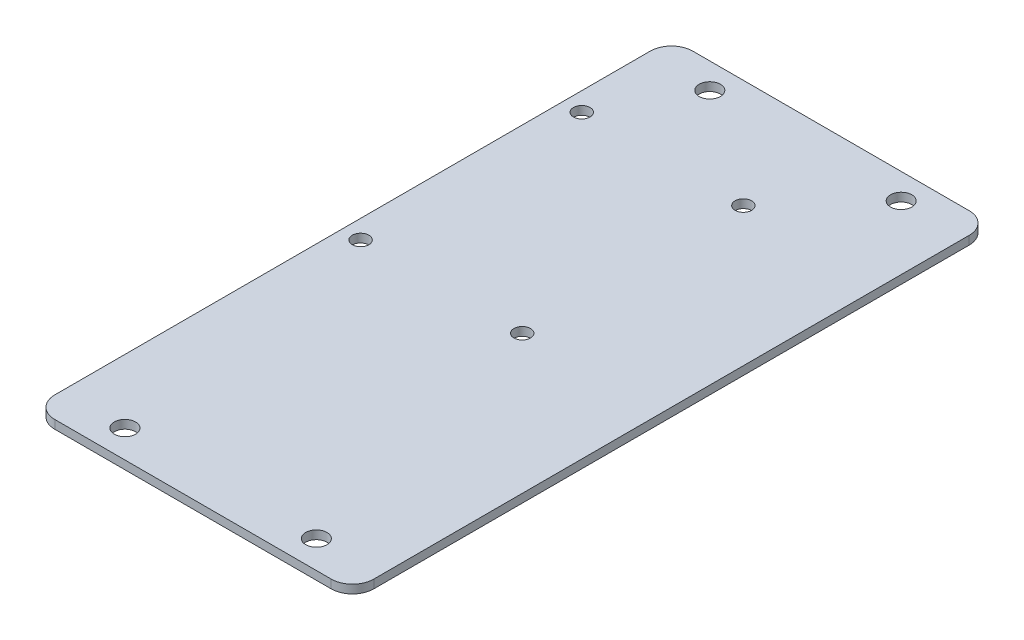
SolidWorks part; units mm, degrees
ref_plane "Front" through (0, 0, 0) normal (0, 0, 1) x (1, 0, 0)
ref_plane "Top" through (0, 0, 0) normal (0, 1, 0) x (1, 0, 0)
ref_plane "Right" through (0, 0, 0) normal (1, 0, 0) x (0, 0, -1)
sketch "Sketch1" plane through (0, 0, 0) normal (0, 1, 0) x (1, 0, 0)
  line L0 (0, 87.63) -> (0, 95.25) construction
  line L1 (-47.625, 95.25) -> (47.625, 95.25)
  line L2 (-47.625, 95.25) -> (-47.625, -95.25)
  line L3 (-47.625, -95.25) -> (47.625, -95.25)
  line L4 (47.625, 95.25) -> (47.625, -95.25)
  line L5 (-47.625, 95.25) -> (47.625, -95.25) construction
  line L6 (-47.625, -95.25) -> (47.625, 95.25) construction
  line L7 (-42.037, 62.865) -> (6.223, 62.865) construction
  line L8 (-42.037, 62.865) -> (-42.037, -3.175) construction
  line L9 (-42.037, -3.175) -> (6.223, -3.175) construction
  line L10 (6.223, 62.865) -> (6.223, -3.175) construction
  line L11 (-42.037, 62.865) -> (6.223, -3.175) construction
  line L12 (-42.037, -3.175) -> (6.223, 62.865) construction
  line L13 (-28.575, 87.63) -> (28.575, 87.63) construction
  line L14 (-28.575, 87.63) -> (-28.575, -86.995) construction
  line L15 (-28.575, -86.995) -> (28.575, -86.995) construction
  line L16 (28.575, 87.63) -> (28.575, -86.995) construction
  circle A0 centre (-42.037, 62.865) radius 2.4765
  circle A1 centre (6.223, 62.865) radius 2.4765
  circle A2 centre (6.223, -3.175) radius 2.4765
  circle A3 centre (-42.037, -3.175) radius 2.4765
  circle A4 centre (-28.575, 87.63) radius 3.175
  circle A5 centre (28.575, 87.63) radius 3.175
  circle A6 centre (28.575, -86.995) radius 3.175
  circle A7 centre (-28.575, -86.995) radius 3.175
  point P0 (0, 0)
  point P6 (-17.907, 29.845)
  point P15 (0, 0)
  point P24 (28.575, 90.0667)
  dimension "D3" = 4.953
  dimension "D8" = 6.35
  dimension "D11" = 24.765
  dimension "D13" = 83.82
  dimension "D1" = 190.5
  dimension "D2" = 95.25
  dimension "D4" = 29.845
  dimension "D5" = 17.907
  dimension "D6" = 66.04
  dimension "D7" = 48.26
  dimension "D9" = 174.625
  dimension "D10" = 57.15
  dimension "D12" = 7.62
extrude "Boss-Extrude1" add sketch "Sketch1" along normal blind 2.54
fillet "Fillet1" radius 6.35 4 edges at (-47.625, 1.27, 95.25) (47.625, 1.27, 95.25) (47.625, 1.27, -95.25) (-47.625, 1.27, -95.25)
